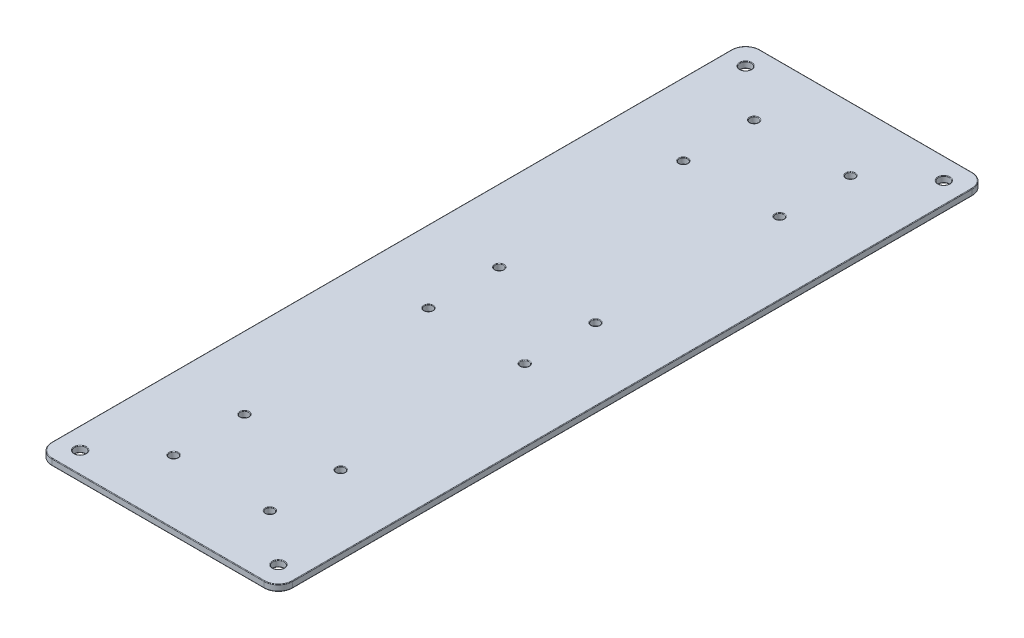
SolidWorks part; units mm, degrees
ref_plane "Front Plane" through (0, 0, 0) normal (0, 0, 1) x (1, 0, 0)
ref_plane "Top Plane" through (0, 0, 0) normal (0, 1, 0) x (1, 0, 0)
ref_plane "Right Plane" through (0, 0, 0) normal (1, 0, 0) x (0, 0, -1)
sketch "Sketch1" plane through (0, 0, 0) normal (0, 1, 0) x (1, 0, 0)
  line L1 (0, 0) -> (85, 0)
  line L2 (0, 0) -> (0, -250)
  line L3 (0, -250) -> (85, -250)
  line L4 (85, 0) -> (85, -250)
  dimension "D1" = 250
  dimension "D2" = 85
extrude "Boss-Extrude1" add sketch "Sketch1" along normal blind 2.25
sketch "Sketch4" plane through (0, 2.25, 0) normal (0, 1, 0) x (1, 0, 0)
  line L0 (0, -125) -> (85, -125) construction
  line L1 (85, 0) -> (0, 0) construction
  line L2 (42.5, 0) -> (42.5, -250) construction
  line L3 (0, -250) -> (85, -250) construction
  line L5 (0, 0) -> (0, -250) construction
  line L7 (85, -250) -> (85, 0) construction
  circle A0 centre (7.5, -7.5) radius 2
  circle A1 centre (77.5, -7.5) radius 2
  circle A4 centre (25.5, -22.5) radius 1.5
  circle A5 centre (59.5, -22.5) radius 1.5
  circle A6 centre (25.5, -47.5) radius 1.5
  circle A7 centre (59.5, -47.5) radius 1.5
  circle A8 centre (25.5, -112.5) radius 1.5
  circle A9 centre (59.5, -112.5) radius 1.5
  circle A10 centre (25.5, -137.5) radius 1.5
  circle A11 centre (59.5, -137.5) radius 1.5
  circle A12 centre (59.5, -202.5) radius 1.5
  circle A13 centre (25.5, -202.5) radius 1.5
  circle A14 centre (59.5, -227.5) radius 1.5
  circle A15 centre (25.5, -227.5) radius 1.5
  circle A16 centre (77.5, -242.5) radius 2
  circle A17 centre (7.5, -242.5) radius 2
  dimension "D1" = 4
  dimension "D4" = 3
  dimension "D2" = 70
  dimension "D3" = 7.5
  dimension "D5" = 34
  dimension "D6" = 17
  dimension "D7" = 35
  dimension "D8" = 25
  dimension "D9" = 25
  dimension "D10" = 22.5
  dimension "D11" = 25
extrude "Cut-Extrude1" cut sketch "Sketch4" against normal up to surface (2.25 mm away) up to face at (42.5, 0, 125)
fillet "Fillet1" radius 5 4 edges at (0, 1.125, 250) (0, 1.125, 0) (85, 1.125, 0) (85, 1.125, 250)
fillet "Fillet3" radius 0.2 48 edges at (7.5, 2.25, 240.5) (7.5, 0, 244.5) (77.5, 2.25, 240.5) (77.5, 0, 244.5) (25.5, 2.25, 226) (25.5, 0, 229) (59.5, 2.25, 226) (59.5, 0, 229) (25.5, 2.25, 201) (25.5, 0, 204) (59.5, 2.25, 201) (59.5, 0, 204) (59.5, 2.25, 139) (59.5, 0, 139) (25.5, 2.25, 139) (25.5, 0, 139) (59.5, 2.25, 114) (59.5, 0, 114) (25.5, 2.25, 114) (25.5, 0, 114) (59.5, 2.25, 49) (59.5, 0, 49) (25.5, 2.25, 49) (25.5, 0, 49) (59.5, 2.25, 24) (59.5, 0, 24) (25.5, 2.25, 24) (25.5, 0, 24) (77.5, 2.25, 9.5) (77.5, 0, 9.5) (7.5, 2.25, 9.5) (7.5, 0, 9.5) (0, 0, 125) (42.5, 0, 250) (85, 0, 125) (42.5, 0, 0) (0, 2.25, 125) (85, 2.25, 125) (42.5, 2.25, 0) (83.5355, 0, 248.5355) (83.5355, 0, 1.4645) (1.4645, 0, 1.4645) (1.4645, 0, 248.5355) (83.5355, 2.25, 248.5355) (83.5355, 2.25, 1.4645) (1.4645, 2.25, 1.4645) (1.4645, 2.25, 248.5355) (42.5, 2.25, 250)
